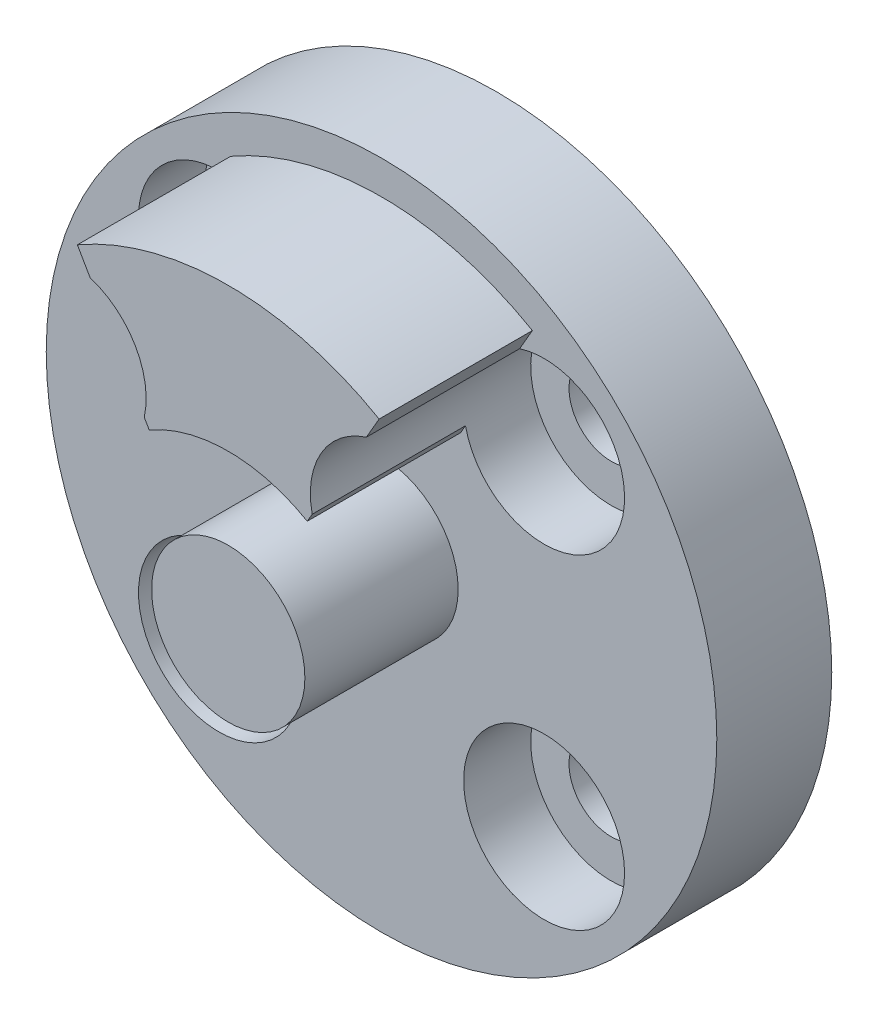
SolidWorks part; units mm, degrees
ref_plane "Front Plane" through (0, 0, 0) normal (0, 0, 1) x (1, 0, 0)
ref_plane "Top Plane" through (0, 0, 0) normal (0, 1, 0) x (1, 0, 0)
ref_plane "Right Plane" through (0, 0, 0) normal (1, 0, 0) x (0, 0, -1)
sketch "Sketch1" plane through (0, 0, 0) normal (0, 0, 1) x (1, 0, 0)
  circle A0 centre (0, 0) radius 17.5
  dimension "D1" = 35
extrude "Boss-Extrude1" add sketch "Sketch1" along normal mid plane 6
sketch "Sketch2" plane through (0, 0, 3) normal (0, 0, 1) x (1, 0, 0)
  line L3 (0, 0) -> (0, 11) construction
  line L4 (7.875, 13.6399) -> (4.125, 7.1447)
  line L5 (-4.125, 7.1447) -> (-7.875, 13.6399)
  arc A1 (4.125, 7.1447) -> (-4.125, 7.1447) centre (0, 0) ccw
  arc A6 (-7.875, 13.6399) -> (7.875, 13.6399) centre (0, 0) cw
  circle A7 centre (0, 0) radius 17.5 construction
  dimension "D2" = 7.5
  dimension "D3" = 1.75
  dimension "D1" = 30
extrude "Boss-Extrude2" add sketch "Sketch2" along normal blind 8
sketch "Sketch3" plane through (0, 0, 3) normal (0, 0, 1) x (1, 0, 0)
  circle A0 centre (0, 0) radius 4
extrude "Boss-Extrude3" add sketch "Sketch3" along normal blind 8
sketch "Sketch4" plane through (0, 0, -3) normal (0, 0, -1) x (-1, 0, 0)
  line L0 (0, 0) -> (-8.4853, 8.4853) construction
  circle A0 centre (0, 0) radius 12 construction
  circle A5 centre (-8.4853, 8.4853) radius 2.2
  circle A7 centre (8.4853, 8.4853) radius 2.2
  circle A8 centre (8.4853, -8.4853) radius 2.2
  circle A9 centre (-8.4853, -8.4853) radius 2.2
  point P14 (0, 0)
  point P17 (0, 0)
  dimension "D1" = 4
extrude "Cut-Extrude1" cut sketch "Sketch4" against normal up to surface (6 mm away) up to face at (4, 0, 3)
sketch "Sketch5" plane through (0, 0, 3) normal (0, 0, 1) x (1, 0, 0)
  circle A0 centre (-8.4853, -8.4853) radius 4.2
  circle A1 centre (-8.4853, 8.4853) radius 4.2
  circle A2 centre (8.4853, 8.4853) radius 4.2
  circle A3 centre (8.4853, -8.4853) radius 4.2
  point P12 (0, 0)
  dimension "D1" = 4
extrude "Cut-Extrude2" cut sketch "Sketch5" against normal blind 3.5 and the other way up to surface other way up to face at (0, 11.1962, 11)
